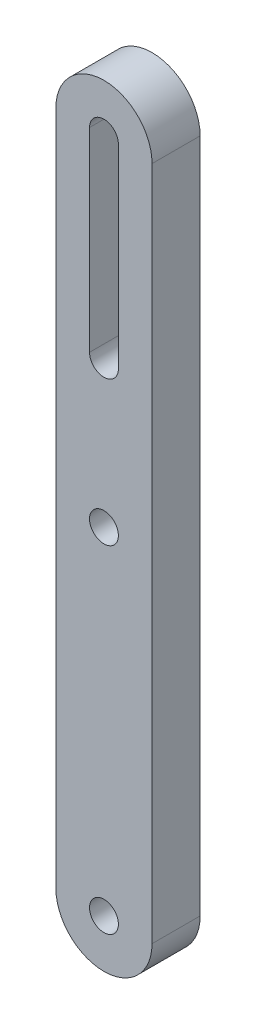
SolidWorks part; units mm, degrees
ref_plane "Alzado" through (0, 0, 0) normal (0, 0, 1) x (1, 0, 0)
ref_plane "Planta" through (0, 0, 0) normal (0, 1, 0) x (1, 0, 0)
ref_plane "Vista lateral" through (0, 0, 0) normal (1, 0, 0) x (0, 0, -1)
sketch "Croquis1" plane through (0, 0, 0) normal (0, 0, 1) x (1, 0, 0)
  line L0 (0, 0) -> (0, -100) construction
  line L1 (5, 0) -> (5, -100)
  line L2 (-5, 0) -> (-5, -100)
  arc A0 (5, 0) -> (-5, 0) centre (0, 0) ccw
  arc A1 (-5, -100) -> (5, -100) centre (0, -100) ccw
  circle A2 centre (0, 0) radius 1.5
  circle A3 centre (0, -100) radius 1.5
  circle A4 centre (0, -65) radius 1.5
  point P3 (0, -50)
  dimension "D2" = 5
  dimension "D3" = 3
  dimension "D1" = 100
  dimension "D4" = 35
extrude "Saliente-Extruir1" add sketch "Croquis1" along normal blind 5
ref_plane "Plano1" through (0, 0, 2.5) normal (0, 0, 1) x (1, 0, 0)
sketch "Croquis7" plane through (0, 0, 2.5) normal (0, 0, 1) x (1, 0, 0)
  point P0 (0, 0)
sketch "Croquis8" plane through (0, 0, 5) normal (0, 0, 1) x (1, 0, 0)
  line L0 (0, 0) -> (0, -50) construction
  line L1 (1.5, 0) -> (1.5, -50)
  line L2 (-1.5, 0) -> (-1.5, -50)
  arc A0 (1.5, 0) -> (-1.5, 0) centre (0, 0) ccw
  arc A1 (-1.5, -50) -> (1.5, -50) centre (0, -50) ccw
  point P3 (0, -25)
  dimension "D1" = 3
  dimension "D2" = 50
extrude "Cortar-Extruir1" cut sketch "Croquis8" against normal blind 10
sketch "Croquis9" plane through (0, 0, 5) normal (0, 0, 1) x (1, 0, 0)
  line L0 (-5, 0) -> (-5, -100) construction
  line L1 (-5, -29.7605) -> (16.7163, -29.7605)
  line L2 (-5, -29.7605) -> (-5, 12.2086)
  line L3 (-5, 12.2086) -> (16.7163, 12.2086)
  line L4 (16.7163, -29.7605) -> (16.7163, 12.2086)
extrude "Cortar-Extruir2" cut sketch "Croquis9" against normal blind 10
sketch "Croquis10" plane through (0, 0, 5) normal (0, 0, 1) x (1, 0, 0)
  line L0 (1.5, -29.7605) -> (5, -29.7605)
  line L1 (-1.5, -29.7588) -> (-5, -29.7588)
  arc A0 (1.5, -29.7605) -> (-1.5, -29.7588) centre (0, -29.7588) ccw
  arc A1 (5, -29.7605) -> (-5, -29.7588) centre (0, -29.7588) ccw
  dimension "D1" = 3
extrude "Saliente-Extruir2" add sketch "Croquis10" against normal blind 5 separate body
sketch "Croquis11" plane through (0, 0, 0) normal (0, 0, -1) x (-1, 0, 0)
  line L0 (-1.5, -50) -> (-1.5, -29.7605) construction
  line L2 (1.5, -29.7588) -> (5, -29.7588)
  line L3 (-5, -29.7605) -> (-1.5, -29.7605)
  line L6 (-5, -29.7605) -> (-5, -32.238)
  line L7 (-5, -32.238) -> (-1.5, -32.238)
  line L8 (-1.5, -29.7605) -> (-1.5, -32.238)
  line L9 (5, -29.7605) -> (5, -100) construction
  line L11 (1.5, -29.7588) -> (1.5, -32.238)
  line L12 (1.5, -32.238) -> (5, -32.238)
  line L13 (5, -29.7588) -> (5, -32.238)
  arc A2 (1.5, -29.7588) -> (-1.5, -29.7605) centre (0, -29.7588) ccw
  arc A3 (5, -29.7588) -> (-5, -29.7605) centre (0, -29.7588) ccw
  arc A4 (1.5, -29.7588) -> (-1.5, -29.7605) centre (0, -29.7588) ccw
  arc A5 (5, -29.7588) -> (-5, -29.7605) centre (0, -29.7588) ccw
  dimension "D1" = 0
extrude "Saliente-Extruir3" add sketch "Croquis11" against normal blind 5
